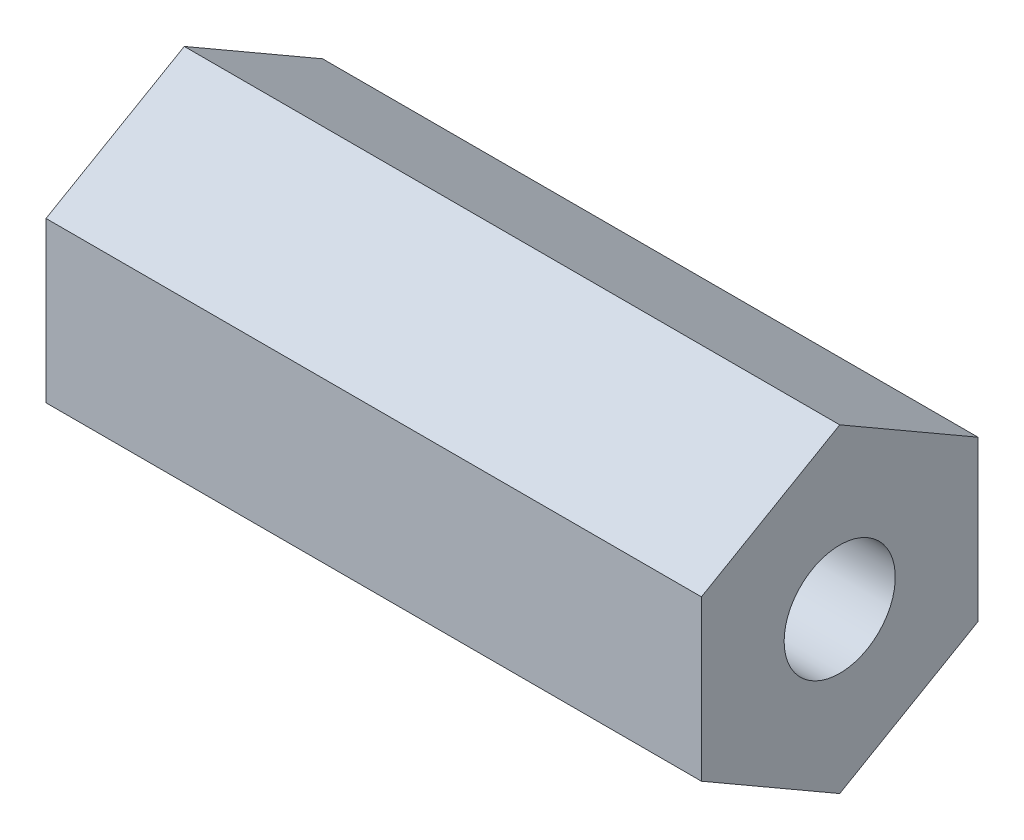
SolidWorks part; units mm, degrees
ref_plane "Front Plane" through (0, 0, 0) normal (0, 0, 1) x (1, 0, 0)
ref_plane "Top Plane" through (0, 0, 0) normal (0, 1, 0) x (1, 0, 0)
ref_plane "Right Plane" through (0, 0, 0) normal (1, 0, 0) x (0, 0, -1)
sketch "Sketch1" plane through (0, 0, 0) normal (1, 0, 0) x (0, 0, -1)
  line L1 (0, 7.3323) -> (-6.35, 3.6662)
  line L2 (-6.35, 3.6662) -> (-6.35, -3.6662)
  line L3 (-6.35, -3.6662) -> (0, -7.3323)
  line L4 (0, -7.3323) -> (6.35, -3.6662)
  line L5 (6.35, -3.6662) -> (6.35, 3.6662)
  line L6 (6.35, 3.6662) -> (0, 7.3323)
  circle A0 centre (0, 0) radius 6.35 construction
  circle A1 centre (0, 0) radius 2.5527
  dimension "D1" = 12.7
  dimension "D2" = 5.1054
extrude "Boss-Extrude1" add sketch "Sketch1" along normal blind 30.099
